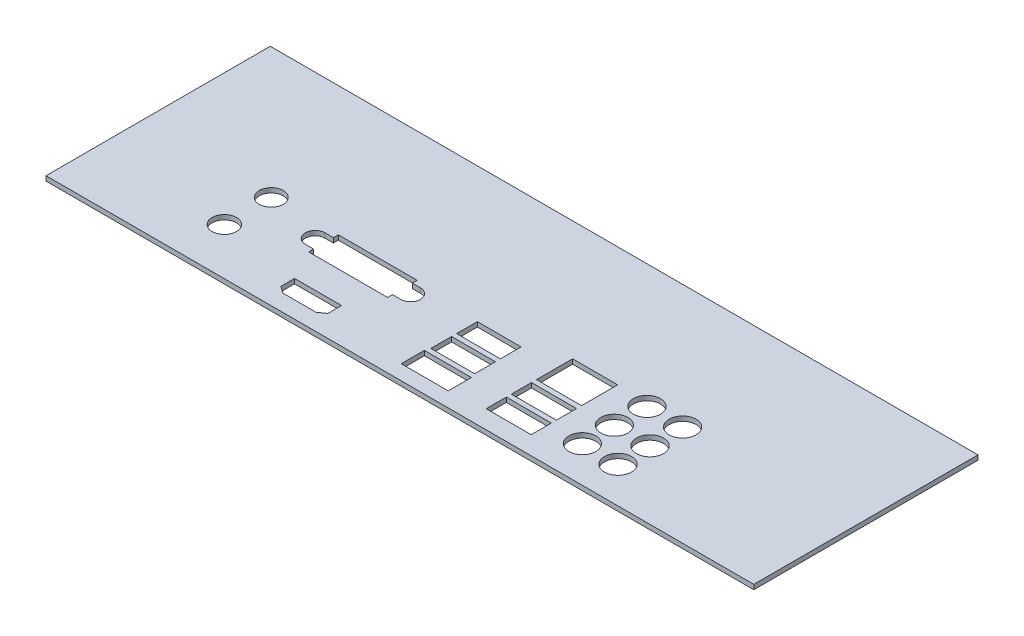
SolidWorks part; units mm, degrees
ref_plane "Front Plane" through (0, 0, 0) normal (0, 0, 1) x (1, 0, 0)
ref_plane "Top Plane" through (0, 0, 0) normal (0, 1, 0) x (1, 0, 0)
ref_plane "Right Plane" through (0, 0, 0) normal (1, 0, 0) x (0, 0, -1)
sketch "Sketch1" plane through (0, 0, 0) normal (0, 1, 0) x (1, 0, 0)
  line L0 (-119.6944, 37.9212) -> (119.6944, -37.9212) construction
  line L1 (-119.6944, 37.9212) -> (119.6944, 37.9212)
  line L2 (-119.6944, 37.9212) -> (-119.6944, -37.9212)
  line L3 (-119.6944, -37.9212) -> (119.6944, -37.9212)
  line L4 (119.6944, 37.9212) -> (119.6944, -37.9212)
  line L5 (119.6944, -37.9212) -> (120.7986, -37.5531) construction
extrude "Boss-Extrude1" add sketch "Sketch1" against normal blind 1.5875
sketch "Sketch2" plane through (0, 0, 0) normal (0, 1, 0) x (1, 0, 0)
  line L0 (-119.6944, 37.9212) -> (-119.6944, -37.9212) construction
  line L1 (-119.6944, -37.9212) -> (119.6944, -37.9212) construction
  point P0 (-75.8114, -6.4108)
  line B0 (-47.5584, -25.978) -> (-31.6834, -25.978)
  line B1 (-31.6834, -25.978) -> (-31.6834, -30.6067)
  line B2 (-31.6834, -30.6067) -> (-34.0329, -32.2518)
  line B3 (-34.0329, -32.2518) -> (-45.2089, -32.2518)
  line B4 (-45.2089, -32.2518) -> (-47.5584, -30.6067)
  line B5 (-47.5584, -30.6067) -> (-47.5584, -25.978)
  line B6 (-52.9559, -14.1543) -> (-52.9559, -15.818)
  line B7 (-52.9559, -15.818) -> (-26.2859, -15.818)
  line B8 (-26.2859, -15.818) -> (-26.2859, -14.1543)
  line B9 (-26.2859, -14.1543) -> (-23.4792, -14.1543)
  line B10 (-23.4792, -7.4487) -> (-26.2859, -7.4487)
  line B11 (-26.2859, -7.4487) -> (-26.2859, -5.785)
  line B12 (-26.2859, -5.785) -> (-52.9559, -5.785)
  line B13 (-52.9559, -5.785) -> (-52.9559, -7.4487)
  line B14 (-52.9559, -7.4487) -> (-55.7626, -7.4487)
  line B15 (-55.7626, -14.1543) -> (-52.9559, -14.1543)
  line B16 (-4.0022, -7.7175) -> (10.806, -7.7175)
  line B17 (-4.0022, -7.7175) -> (-4.0022, -14.7279)
  line B18 (-4.0022, -14.7279) -> (10.806, -14.7279)
  line B19 (10.806, -7.7175) -> (10.806, -14.7279)
  line B20 (-4.0022, -16.4297) -> (10.806, -16.4297)
  line B21 (-4.0022, -16.4297) -> (-4.0022, -23.4401)
  line B22 (-4.0022, -23.4401) -> (10.806, -23.4401)
  line B23 (10.806, -16.4297) -> (10.806, -23.4401)
  line B24 (-4.5483, -25.0911) -> (11.3521, -25.0911)
  line B25 (-4.5483, -25.0911) -> (-4.5483, -32.9143)
  line B26 (-4.5483, -32.9143) -> (11.3521, -32.9143)
  line B27 (11.3521, -25.0911) -> (11.3521, -32.9143)
  line B28 (22.9901, -2.4882) -> (38.2301, -2.4882)
  line B29 (22.9901, -2.4882) -> (22.9901, -14.7056)
  line B30 (22.9901, -14.7056) -> (38.2301, -14.7056)
  line B31 (38.2301, -2.4882) -> (38.2301, -14.7056)
  line B32 (22.9901, -16.4074) -> (38.2301, -16.4074)
  line B33 (22.9901, -16.4074) -> (22.9901, -23.2146)
  line B34 (22.9901, -23.2146) -> (38.2301, -23.2146)
  line B35 (38.2301, -16.4074) -> (38.2301, -23.2146)
  line B36 (22.9901, -24.9164) -> (38.2301, -24.9164)
  line B37 (22.9901, -24.9164) -> (22.9901, -31.7236)
  line B38 (22.9901, -31.7236) -> (38.2301, -31.7236)
  line B39 (38.2301, -24.9164) -> (38.2301, -31.7236)
  arc B40 (-55.7626, -7.4487) -> (-55.7626, -14.1543) centre (-55.7626, -10.8015) ccw
  arc B41 (-23.4792, -14.1543) -> (-23.4792, -7.4487) centre (-23.4792, -10.8015) ccw
  circle B42 centre (-75.2444, -22.0462) radius 4.1275
  circle B43 centre (49.5077, -25.7134) radius 4.572
  circle B44 centre (-75.2444, -6.1712) radius 4.0513
  circle B45 centre (49.5077, -3.8694) radius 4.572
  circle B46 centre (61.5727, -3.8694) radius 4.572
  circle B47 centre (49.5077, -14.893) radius 4.572
  circle B48 centre (61.5727, -14.893) radius 4.572
  circle B49 centre (61.5727, -25.7134) radius 4.572
  dimension "D1" = 44.45
  dimension "D2" = 31.75
sketch_block_instance "Block10.2-1"
sketch_block "Block10.2" parameters "D1"=8.1026, "D2"=9.144, "D3"=8.255, "D4"=6.7056, "D5"=10.033, "D6"=15.875, "D7"=6.2738, "D8"=26.67, "D9"=38.989, "D10"=35, "D11"=10.16, "D12"=11.176, "D13"=15.9004, "D14"=14.8082, "D15"=1.651, "D16"=1.7018, "D17"=7.8232, "D18"=7.0104, "D19"=1.7018, "D20"=1.7018, "D21"=12.2174, "D22"=6.8072, "D23"=15.24, "D24"=5.2293, "D25"=12.065, "D26"=10.8204, "D27"=11.0236
extrude "Cut-Extrude1" cut sketch "Sketch2" against normal up to next
